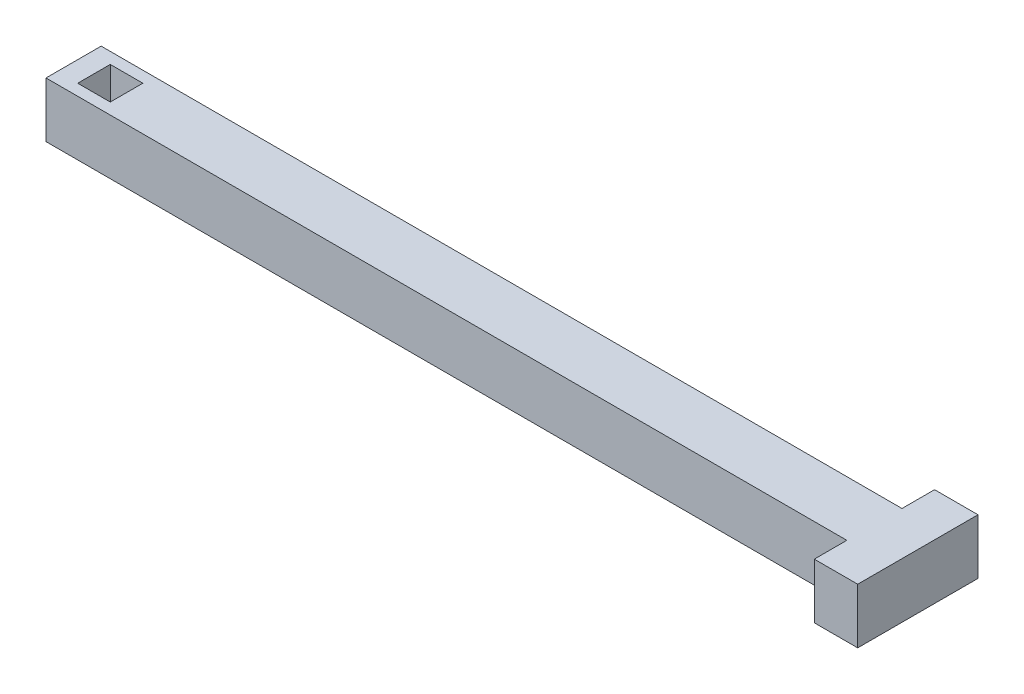
SolidWorks part; units mm, degrees
ref_plane "Front Plane" through (0, 0, 0) normal (0, 0, 1) x (1, 0, 0)
ref_plane "Top Plane" through (0, 0, 0) normal (0, 1, 0) x (1, 0, 0)
ref_plane "Right Plane" through (0, 0, 0) normal (1, 0, 0) x (0, 0, -1)
sketch "Sketch1" plane through (0, 0, 0) normal (0, 1, 0) x (1, 0, 0)
  line L0 (18.44, 1.27) -> (18.44, 2.77)
  line L1 (18.44, -1.27) -> (-18.44, -1.27)
  line L3 (18.44, 1.27) -> (-18.44, 1.27)
  line L4 (-18.44, -1.27) -> (-18.44, 1.27)
  line L5 (18.44, 2.77) -> (20.44, 2.77)
  line L6 (20.44, 2.77) -> (20.44, -2.77)
  line L7 (20.44, -2.77) -> (18.44, -2.77)
  line L8 (18.44, -2.77) -> (18.44, -1.27)
  line L10 (-17.5, 0.75) -> (-16, 0.75)
  line L11 (-17.5, 0.75) -> (-17.5, -0.75)
  line L12 (-17.5, -0.75) -> (-16, -0.75)
  line L13 (-16, 0.75) -> (-16, -0.75)
  circle A0 centre (-16.75, 0) radius 0.75 construction
  point P0 (0, 0)
  point P6 (0, 1.27)
  point P7 (-18.44, 0)
  dimension "D5" = 1.5
  dimension "D1" = 36.88
  dimension "D2" = 2
  dimension "D3" = 2.54
  dimension "D4" = 16.75
  dimension "D6" = 1.5
extrude "Boss-Extrude1" add sketch "Sketch1" along normal blind 2.54
